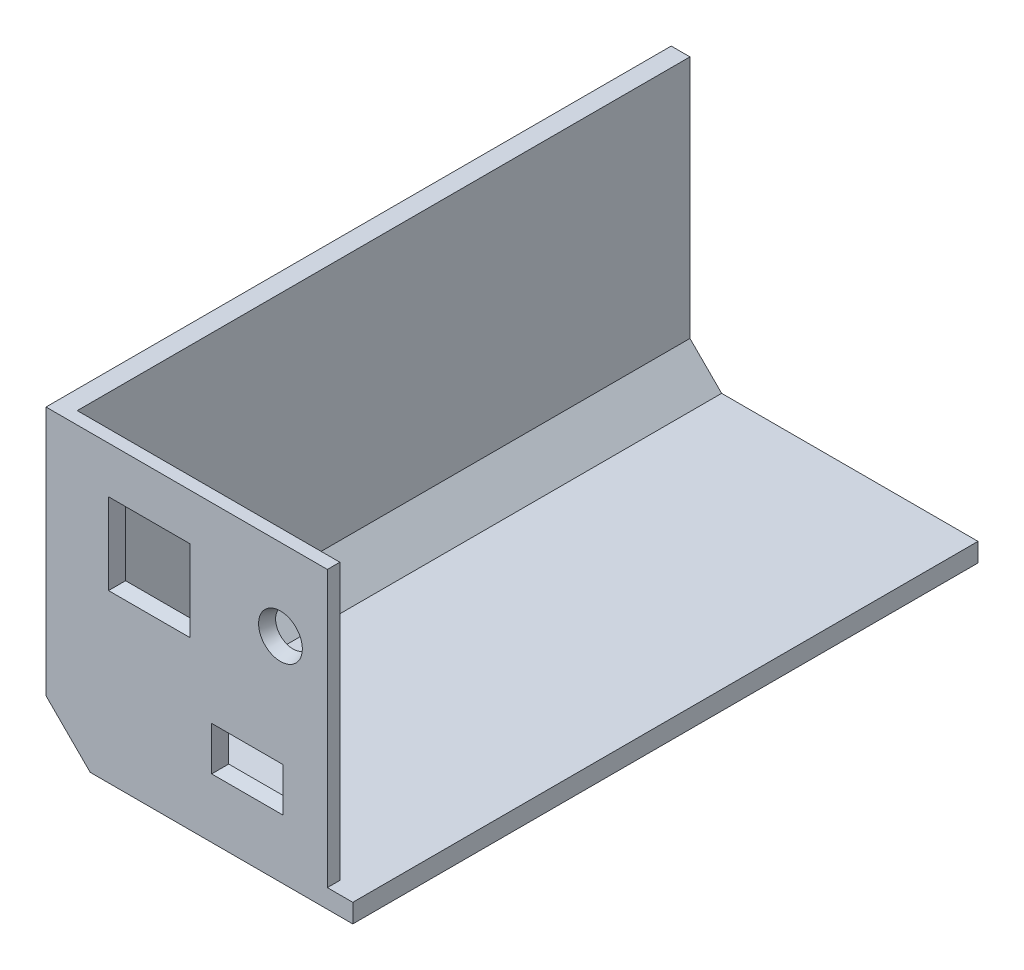
SolidWorks part; units mm, degrees
ref_plane "Front Plane" through (0, 0, 0) normal (0, 0, 1) x (1, 0, 0)
ref_plane "Top Plane" through (0, 0, 0) normal (0, 1, 0) x (1, 0, 0)
ref_plane "Right Plane" through (0, 0, 0) normal (1, 0, 0) x (0, 0, -1)
sketch "Sketch2" plane through (0, 0, 0) normal (0, 0, 1) x (1, 0, 0)
  line L0 (-7.0711, 47.0738) -> (-4.0711, 47.0738)
  line L7 (42, 3) -> (42, 0)
  line L8 (-4.0711, 47.0738) -> (-4.0711, 8.0711)
  line L9 (-4.0711, 8.0711) -> (1, 3)
  line L10 (1, 3) -> (42, 3)
  line L11 (-7.0711, 47.0738) -> (-7.0711, 7.0711)
  line L12 (-7.0711, 7.0711) -> (0, 0)
  line L13 (0, 0) -> (42, 0)
  point P0 (0, 0)
  dimension "D1" = 3
  dimension "D2" = 3
  dimension "D3" = 42
  dimension "D4" = 41
  dimension "D5" = 10
  dimension "D6" = 135
extrude "Boss-Extrude1" add sketch "Sketch2" along normal blind 100
sketch "Sketch3" plane through (0, 0, 100) normal (0, 0, 1) x (1, 0, 0)
  line L1 (-4.0711, 47.0738) -> (37.9289, 47.0738)
  line L4 (37.9289, 47.0738) -> (37.9289, 3)
  line L5 (-4.0711, 47.0738) -> (37.9289, 3) construction
  line L6 (-4.0711, 47.0738) -> (-4.0711, 8.0711)
  line L8 (-4.0711, 8.0711) -> (1, 3)
  line L9 (1, 3) -> (37.9289, 3)
  line L10 (-4.0711, 47.0738) -> (-7.0711, 47.0738) construction
  point P0 (17.0483, 24.9116)
  dimension "D2" = 42
extrude "Boss-Extrude2" add sketch "Sketch3" against normal blind 2
sketch "Sketch4" plane through (0, 0, 100) normal (0, 0, 1) x (1, 0, 0)
  line L0 (37.9289, 3) -> (37.9289, 47.0738) construction
  line L1 (37.9289, 47.0738) -> (-7.0711, 47.0738) construction
  circle A0 centre (30.4289, 34.0738) radius 2.75
  dimension "D1" = 5.5
  dimension "D2" = 7.5
  dimension "D3" = 13
extrude "Cut-Extrude2" cut sketch "Sketch4" against normal up to next
sketch "Sketch5" plane through (0, 0, 100) normal (0, 0, 1) x (1, 0, 0)
  line L1 (20.9289, 15) -> (29.9289, 15)
  line L2 (20.9289, 15) -> (20.9289, 11)
  line L3 (20.9289, 11) -> (29.9289, 11)
  line L4 (29.9289, 15) -> (29.9289, 11)
  line L5 (20.9289, 15) -> (29.9289, 11) construction
  line L6 (20.9289, 11) -> (29.9289, 15) construction
  line L10 (37.9289, 3) -> (37.9289, 47.0738) construction
  point P0 (25.4289, 13)
  dimension "D1" = 4
  dimension "D2" = 12.5
extrude "Cut-Extrude3" cut sketch "Sketch5" against normal up to next
sketch "Sketch6" plane through (0, 0, 100) normal (0, 0, 1) x (1, 0, 0)
  line L0 (-7.0711, 47.0738) -> (-7.0711, 7.0711) construction
  line L1 (4.4289, 38.144) -> (14.4289, 38.144)
  line L2 (4.4289, 38.144) -> (4.4289, 28.144)
  line L3 (4.4289, 28.144) -> (14.4289, 28.144)
  line L4 (14.4289, 38.144) -> (14.4289, 28.144)
  line L5 (4.4289, 38.144) -> (14.4289, 28.144) construction
  line L6 (4.4289, 28.144) -> (14.4289, 38.144) construction
  point P0 (9.4289, 33.144)
  dimension "D1" = 10
  dimension "D2" = 16.5
extrude "Cut-Extrude4" cut sketch "Sketch6" against normal up to next
sketch "Sketch7" plane through (0, 0, 100) normal (0, 0, 1) x (1, 0, 0)
  line L0 (20.9289, 15) -> (20.9289, 11) construction
  line L1 (19.4289, 16.5) -> (30.876, 16.5)
  line L2 (19.4289, 16.5) -> (19.4289, 9.5)
  line L3 (19.4289, 9.5) -> (30.876, 9.5)
  line L4 (30.876, 16.5) -> (30.876, 9.5)
  line L5 (19.4289, 16.5) -> (30.876, 9.5) construction
  line L6 (19.4289, 9.5) -> (30.876, 16.5) construction
  line L7 (29.9289, 15) -> (20.9289, 15) construction
  line L8 (20.9289, 11) -> (29.9289, 11) construction
  line L9 (14.4289, 38.144) -> (4.4289, 38.144) construction
  line L10 (2.9289, 39.644) -> (15.9289, 39.644)
  line L11 (2.9289, 39.644) -> (2.9289, 26.644)
  line L12 (2.9289, 26.644) -> (15.9289, 26.644)
  line L13 (15.9289, 39.644) -> (15.9289, 26.644)
  line L14 (2.9289, 39.644) -> (15.9289, 26.644) construction
  line L15 (2.9289, 26.644) -> (15.9289, 39.644) construction
  line L16 (4.4289, 28.144) -> (14.4289, 28.144) construction
  line L17 (14.4289, 28.144) -> (14.4289, 38.144) construction
  circle A0 centre (30.4289, 34.0738) radius 3.5
  point P3 (25.1524, 13)
  point P14 (9.4289, 33.144)
  dimension "D1" = 7
  dimension "D2" = 1.5
  dimension "D3" = 11.447
  dimension "D4" = 1.5
  dimension "D5" = 1.5
  dimension "D6" = 1.5
  dimension "D7" = 1.5
  dimension "D8" = 1.5
extrude "Cut-Extrude6" cut sketch "Sketch7" against normal up to next (2 mm away) draft 20
